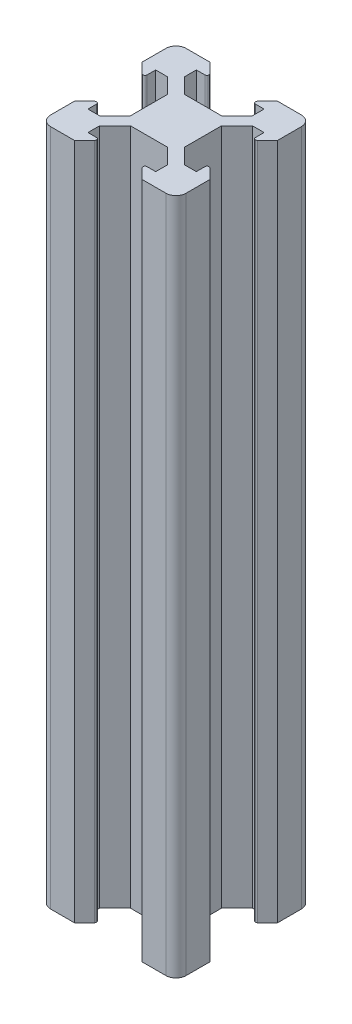
SolidWorks part; units mm, degrees
ref_plane "Спереди" through (0, 0, 0) normal (0, 0, 1) x (1, 0, 0)
ref_plane "Сверху" through (0, 0, 0) normal (0, 1, 0) x (1, 0, 0)
ref_plane "Справа" through (0, 0, 0) normal (1, 0, 0) x (0, 0, -1)
sketch "Эскиз1" plane through (0, 0, 0) normal (0, 1, 0) x (1, 0, 0)
  line L0 (8, 5) -> (6.2728, 5)
  line L1 (8.5, 10) -> (-8.5, 10)
  line L2 (10, 8.5) -> (10, -8.5)
  line L3 (8.5, -10) -> (-8.5, -10)
  line L4 (-10, 8.5) -> (-10, -8.5)
  line L5 (10, 10) -> (-10, -10) construction
  line L6 (10, -10) -> (-10, 10) construction
  line L7 (5, -10) -> (3.5121, -8.5121)
  line L8 (8, 5) -> (5, 5)
  line L9 (8, 5) -> (8, 3.7243)
  line L10 (8, -5) -> (6.2728, -5)
  line L11 (10, 5) -> (8.5121, 3.5121)
  line L12 (8, -5) -> (8, -3.7243)
  line L13 (10, 0) -> (-10, 0) construction
  line L14 (10, -5) -> (8.5121, -3.5121)
  line L15 (5, -8) -> (3.7243, -8)
  line L16 (5, -8) -> (5, -6.2728)
  line L17 (5, -6.2728) -> (2.7272, -4)
  line L18 (2.7272, -4) -> (-2.7272, -4)
  line L19 (-2.7272, -4) -> (-5, -6.2728)
  line L20 (-5, -8) -> (-5, -6.2728)
  line L21 (-5, -8) -> (-3.7243, -8)
  line L22 (-5, -10) -> (-3.5121, -8.5121)
  line L23 (-10, -5) -> (-8.5121, -3.5121)
  line L24 (-8, -5) -> (-8, -3.7243)
  line L25 (-8, -5) -> (-6.2728, -5)
  line L26 (-6.2728, -5) -> (-4, -2.7272)
  line L27 (-4, -2.7272) -> (-4, 2.7272)
  line L28 (-4, 2.7272) -> (-6.2728, 5)
  line L29 (-8, 5) -> (-6.2728, 5)
  line L30 (-8, 5) -> (-8, 3.7243)
  line L31 (-10, 5) -> (-8.5121, 3.5121)
  line L32 (-5, 10) -> (-3.5121, 8.5121)
  line L33 (-5, 8) -> (-3.7243, 8)
  line L34 (-5, 8) -> (-5, 6.2728)
  line L35 (-5, 6.2728) -> (-2.7272, 4)
  line L36 (6.2728, 5) -> (4, 2.7272)
  line L37 (-2.7272, 4) -> (2.7272, 4)
  line L38 (4, -2.7272) -> (6.2728, -5)
  line L39 (2.7272, 4) -> (5, 6.2728)
  line L40 (4, 2.7272) -> (4, -2.7272)
  line L41 (5, 8) -> (5, 6.2728)
  line L42 (5, 10) -> (5, 4) [skipped]
  line L43 (5, 8) -> (3, 8) [skipped]
  line L44 (5, 10) -> (3, 8) [skipped]
  line L45 (5, -10) -> (5, -4) [skipped]
  line L46 (5, -10) -> (3, -8) [skipped]
  line L47 (5, -8) -> (3, -8) [skipped]
  line L48 (-5, -10) -> (-5, -4) [skipped]
  line L49 (-5, -8) -> (-3, -8) [skipped]
  line L50 (-5, -10) -> (-3, -8) [skipped]
  line L51 (-10, -5) -> (-4, -5) [skipped]
  line L52 (-8, 5) -> (-8, 3) [skipped]
  line L53 (-10, 5) -> (-4, 5) [skipped]
  line L54 (-5, 10) -> (-5, 4) [skipped]
  line L55 (-5, 8) -> (-3, 8) [skipped]
  line L56 (-5, 10) -> (-3, 8) [skipped]
  line L57 (-10, 5) -> (-8, 3) [skipped]
  line L58 (-8, -5) -> (-8, -3) [skipped]
  line L59 (-10, -5) -> (-8, -3) [skipped]
  line L60 (5, 8) -> (3.7243, 8)
  line L61 (5, 10) -> (3.5121, 8.5121)
  arc A0 (-8.5, -10) -> (-10, -8.5) centre (-8.5, -8.5) cw
  arc A1 (-8.5, 10) -> (-10, 8.5) centre (-8.5, 8.5) ccw
  arc A2 (10, -8.5) -> (8.5, -10) centre (8.5, -8.5) cw
  arc A3 (8.5, 10) -> (10, 8.5) centre (8.5, 8.5) cw
  arc A4 (8, 3.7243) -> (8.5121, 3.5121) centre (8.3, 3.7243) ccw
  arc A5 (8, -3.7243) -> (8.5121, -3.5121) centre (8.3, -3.7243) cw
  arc A6 (-8, 3.7243) -> (-8.5121, 3.5121) centre (-8.3, 3.7243) cw
  arc A7 (-8.5121, -3.5121) -> (-8, -3.7243) centre (-8.3, -3.7243) cw
  arc A8 (-3.7243, -8) -> (-3.5121, -8.5121) centre (-3.7243, -8.3) cw
  arc A9 (3.5121, -8.5121) -> (3.7243, -8) centre (3.7243, -8.3) cw
  arc A10 (3.7243, 8) -> (3.5121, 8.5121) centre (3.7243, 8.3) cw
  arc A11 (-3.7243, 8) -> (-3.5121, 8.5121) centre (-3.7243, 8.3) ccw
  point P0 (0, 0)
  point P12 (4, 0)
  point P20 (0, 0)
  point P21 (0, 0)
  point P29 (0, 0)
  point P33 (0, 0)
  point P38 (0, 0)
  point P45 (0, 0)
  point P47 (0, 0)
  point P96 (0, 0)
  point P108 (8, 3)
  point P111 (8, -3)
  dimension "D13" = 1.5
  dimension "D14" = 0.3
  dimension "D1" = 3
  dimension "D2" = 2
  dimension "D3" = 5
  dimension "D4" = 6
  dimension "D5" = 20
  dimension "D6" = 20
  dimension "D8" = 0.9
  dimension "D9" = 0.9
  dimension "D10" = 3.7272
  dimension "D11" = 5
  dimension "D7" = 4
  dimension "D12" = 4
extrude "Бобышка-Вытянуть1" add sketch "Эскиз1" along normal blind 100
